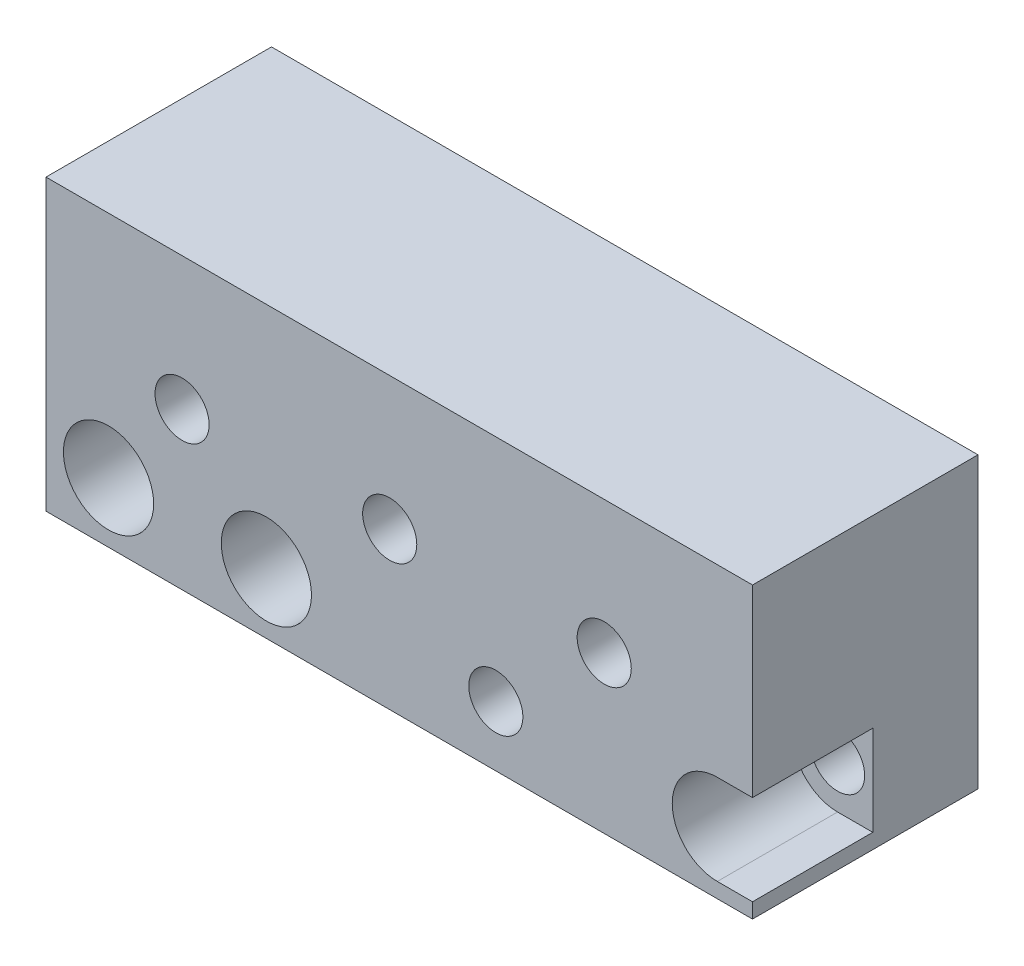
SolidWorks part; units mm, degrees
ref_plane "前视基准面" through (0, 0, 0) normal (0, 0, 1) x (1, 0, 0)
ref_plane "上视基准面" through (0, 0, 0) normal (0, 1, 0) x (1, 0, 0)
ref_plane "右视基准面" through (0, 0, 0) normal (1, 0, 0) x (0, 0, -1)
sketch "草图1" plane through (0, 0, 0) normal (0, 0, 1) x (1, 0, 0)
  line L1 (-21.068, 14.2718) -> (25.932, 14.2718)
  line L2 (-21.068, 14.2718) -> (-21.068, -5.7282)
  line L3 (-21.068, -5.7282) -> (25.932, -5.7282)
  line L4 (25.932, 14.2718) -> (25.932, -5.7282)
  dimension "D1" = 20
  dimension "D2" = 47
extrude "凸台-拉伸1" add sketch "草图1" along normal blind 15
sketch "草图2" plane through (0, 0, 15) normal (0, 0, 1) x (1, 0, 0)
  circle A2 centre (-16.9087, -0.9782) radius 1.8
  circle A4 centre (-6.4087, -0.9782) radius 1.8
  circle A6 centre (22.5913, -0.9782) radius 1.8
  dimension "D1" = 3.6
  dimension "D2" = 3.6
  dimension "D3" = 3.6
extrude "切除-拉伸1" cut sketch "草图2" against normal through all
sketch "草图3" plane through (0, 0, 15) normal (0, 0, 1) x (1, 0, 0)
  circle A0 centre (-16.9087, -0.9782) radius 3
  circle A1 centre (-6.4087, -0.9782) radius 3
  circle A2 centre (22.5913, -0.9782) radius 3
  dimension "D1" = 6
  dimension "D2" = 6
  dimension "D3" = 6
extrude "切除-拉伸2" cut sketch "草图3" against normal blind 8
sketch "草图4" plane through (0, 0, 15) normal (0, 0, 1) x (1, 0, 0)
  circle A0 centre (8.8562, -0.9782) radius 1.8
  circle A1 centre (-12.0159, 5.4264) radius 1.8
  circle A2 centre (1.7972, 5.4264) radius 1.8
  circle A3 centre (16.0675, 5.4264) radius 1.8
  dimension "D1" = 3.6
  dimension "D2" = 3.6
  dimension "D3" = 3.6
  dimension "D4" = 3.6
extrude "切除-拉伸3" cut sketch "草图4" against normal blind 28
sketch "草图5" plane through (0, 0, 0) normal (0, 0, -1) x (-1, 0, 0)
  line L1 (-11.6562, 0.6384) -> (-11.6562, -2.5947)
  line L2 (-11.6562, -2.5947) -> (-8.8562, -4.2113)
  line L3 (-8.8562, -4.2113) -> (-6.0562, -2.5947)
  line L4 (-6.0562, -2.5947) -> (-6.0562, 0.6384)
  line L5 (-6.0562, 0.6384) -> (-8.8562, 2.255)
  line L6 (-8.8562, 2.255) -> (-11.6562, 0.6384)
  line L25 (-17.684, 2.6264) -> (-14.4509, 2.6264)
  line L26 (-14.4509, 2.6264) -> (-12.8343, 5.4264)
  line L27 (-12.8343, 5.4264) -> (-14.4509, 8.2264)
  line L28 (-14.4509, 8.2264) -> (-17.684, 8.2264)
  line L29 (-17.684, 8.2264) -> (-19.3006, 5.4264)
  line L30 (-19.3006, 5.4264) -> (-17.684, 2.6264)
  line L31 (-3.4138, 2.6264) -> (-0.1807, 2.6264)
  line L32 (-0.1807, 2.6264) -> (1.4359, 5.4264)
  line L33 (1.4359, 5.4264) -> (-0.1807, 8.2264)
  line L34 (-0.1807, 8.2264) -> (-3.4138, 8.2264)
  line L35 (-3.4138, 8.2264) -> (-5.0304, 5.4264)
  line L36 (-5.0304, 5.4264) -> (-3.4138, 2.6264)
  line L37 (10.3993, 2.6264) -> (13.6325, 2.6264)
  line L38 (13.6325, 2.6264) -> (15.2491, 5.4264)
  line L39 (15.2491, 5.4264) -> (13.6325, 8.2264)
  line L40 (13.6325, 8.2264) -> (10.3993, 8.2264)
  line L41 (10.3993, 8.2264) -> (8.7828, 5.4264)
  line L42 (8.7828, 5.4264) -> (10.3993, 2.6264)
  circle A0 centre (-8.8562, -0.9782) radius 2.8 construction
  circle A1 centre (-16.0675, 5.4264) radius 2.8 construction
  circle A2 centre (-1.7972, 5.4264) radius 2.8 construction
  circle A3 centre (12.0159, 5.4264) radius 2.8 construction
extrude "切除-拉伸4" cut sketch "草图5" against normal blind 8
sketch "草图6" plane through (0, 0, 15) normal (0, 0, 1) x (1, 0, 0)
  line L0 (-21.068, 14.2718) -> (-21.068, -5.7282) construction
  line L1 (25.932, -5.7282) -> (-21.068, -5.7282)
  line L2 (25.932, -5.7282) -> (25.932, -4.9782)
  line L3 (25.932, -4.9782) -> (-21.068, -4.9782)
  line L4 (-21.068, -5.7282) -> (-21.068, -4.9782)
  line L5 (-19.9087, -4.9782) -> (-52.2244, -4.9782) construction
extrude "切除-拉伸5" cut sketch "草图6" against normal through all
ref_plane "基准面1" through (0, 24.2718, 0) normal (0, 1, 0) x (1, 0, 0)
sketch "草图8" plane through (0, 0, 15) normal (0, 0, 1) x (1, 0, 0)
  line L1 (25.932, -4.9782) -> (18.8862, -4.9782)
  line L2 (25.932, -4.9782) -> (25.932, 3.2374)
  line L3 (25.932, 3.2374) -> (18.8862, 3.2374)
  line L4 (18.8862, -4.9782) -> (18.8862, 3.2374)
extrude "凸台-拉伸2" add sketch "草图8" against normal through all
sketch "草图7" plane through (0, 0, 15) normal (0, 0, 1) x (1, 0, 0)
  line L0 (25.932, -4.9782) -> (25.932, 14.2718) construction
  circle A0 centre (23.5913, -0.9782) radius 1.8
  dimension "D1" = 2.3408
extrude "切除-拉伸6" cut sketch "草图7" against normal through all
sketch "草图9" plane through (0, 0, 15) normal (0, 0, 1) x (1, 0, 0)
  circle A0 centre (23.5913, -0.9782) radius 3
  dimension "D1" = 6
extrude "切除-拉伸7" cut sketch "草图9" against normal blind 8
sketch "草图10" plane through (0, 0, 15) normal (0, 0, 1) x (1, 0, 0)
  line L0 (23.5913, 2.0218) -> (25.932, 2.0218)
  line L1 (25.932, 0.8982) -> (25.932, 14.2718) construction
  line L2 (25.932, 2.0218) -> (25.932, -3.9782)
  line L3 (25.932, -4.9782) -> (25.932, -2.8545) construction
  line L4 (25.932, -3.9782) -> (23.5913, -3.9782)
  line L5 (23.5913, -3.9782) -> (23.5913, 2.0218)
  arc A0 (25.932, 0.8982) -> (25.932, -2.8545) centre (23.5913, -0.9782) ccw construction
  arc A1 (25.932, 0.8982) -> (25.932, -2.8545) centre (23.5913, -0.9782) ccw construction
extrude "切除-拉伸8" cut sketch "草图10" against normal up to surface (8 mm away) up to face at (25.3913, -0.9782, 7)
